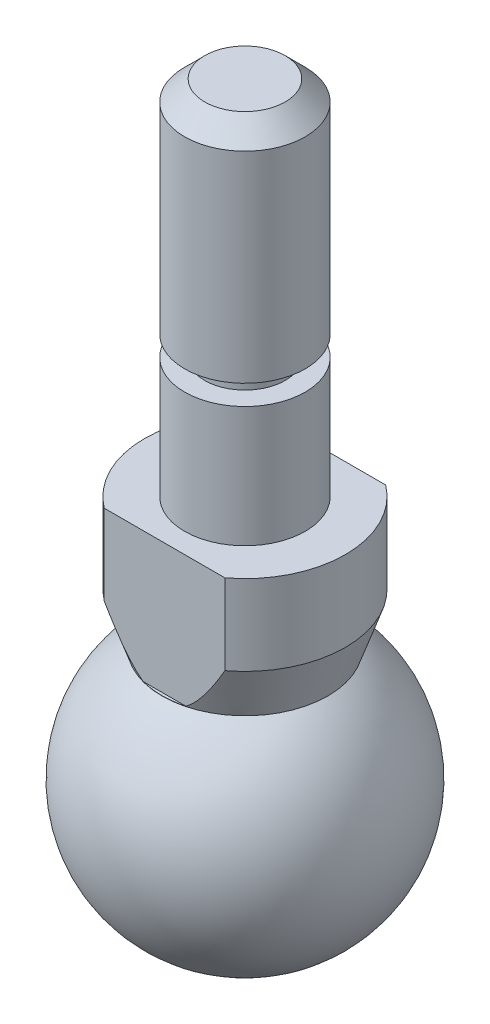
SolidWorks part; units mm, degrees
ref_plane "前视基准面" through (0, 0, 0) normal (0, 0, 1) x (1, 0, 0)
ref_plane "上视基准面" through (0, 0, 0) normal (0, 1, 0) x (1, 0, 0)
ref_plane "右视基准面" through (0, 0, 0) normal (1, 0, 0) x (0, 0, -1)
other "Configuration Table"
sketch "草图1" plane through (0, 0, 0) normal (0, 0, 1) x (1, 0, 0)
  line L0 (0, -16.8267) -> (0, 30.9944) construction
  line L1 (4.1317, 5.6506) -> (5, 8.175)
  line L2 (5, 8.175) -> (5, 12.175)
  line L3 (5, 12.175) -> (3, 12.175)
  line L4 (3, 12.175) -> (3, 18.175)
  line L5 (3, 18.175) -> (2, 18.175)
  line L6 (2, 18.175) -> (2, 19.175)
  line L7 (2, 19.175) -> (3, 19.175)
  line L8 (3, 19.175) -> (3, 30.175)
  line L9 (3, 30.175) -> (0, 30.175)
  line L10 (4.1317, 5.6506) -> (0, 5.6506) construction
  line L11 (0, 0) -> (13.7343, 0) construction
  line L12 (0, 3.375) -> (26.8919, 3.375) construction
  line L13 (0, 3.375) -> (0, -3.375) construction
  line L14 (0, -3.375) -> (26.8919, -3.375) construction
  line L15 (26.8919, 3.375) -> (26.8919, -3.375) construction
  line L16 (0, 0) -> (6.1326, 3.375) construction
  line L17 (0, 0) -> (4.1317, 5.6506) construction
  line L18 (0, 30.175) -> (0, -7)
  arc A0 (0, -7) -> (4.1317, 5.6506) centre (0, 0) ccw
  dimension "D1" = 26.8
  dimension "D10" = 14
  dimension "D2" = 5
  dimension "D3" = 3
  dimension "D4" = 3
  dimension "D5" = 1
  dimension "D6" = 11
  dimension "D7" = 3.375
  dimension "D8" = 3.375
  dimension "D9" = 25
  dimension "D11" = 8.8
  dimension "D12" = 4
  dimension "D13" = 1
revolve "旋转1" add sketch "草图1" angle 360 about L18
chamfer "倒角1" distance 1 angle 45 1 edges at (0, 30.175, 3)
sketch "草图2" plane through (0, 12.175, 0) normal (0, 1, 0) x (1, 0, 0)
  line L0 (0, 0) -> (9.9097, 0) construction
  line L1 (7.7141, -7.8731) -> (7.7141, -4)
  line L2 (-5.4269, 7.8731) -> (7.7141, 7.8731)
  line L3 (-5.4269, 7.8731) -> (-5.4269, 4)
  line L4 (-5.4269, 4) -> (7.7141, 4)
  line L5 (7.7141, 7.8731) -> (7.7141, 4)
  line L6 (-5.4269, -4) -> (7.7141, -4)
  line L7 (-5.4269, -7.8731) -> (-5.4269, -4)
  line L8 (-5.4269, -7.8731) -> (7.7141, -7.8731)
  dimension "D1" = 4
extrude "切除-拉伸1" cut sketch "草图2" against normal blind 6.5
